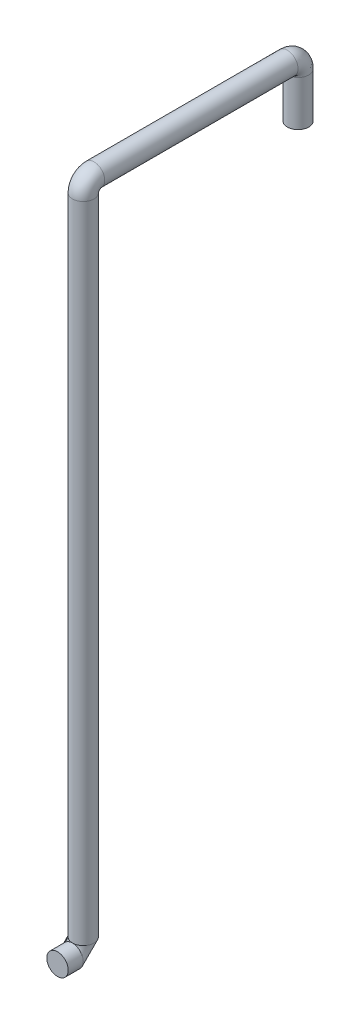
SolidWorks part; units mm, degrees
ref_plane "Alzado" through (0, 0, 0) normal (0, 0, 1) x (1, 0, 0)
ref_plane "Planta" through (0, 0, 0) normal (0, 1, 0) x (1, 0, 0)
ref_plane "Vista lateral" through (0, 0, 0) normal (1, 0, 0) x (0, 0, -1)
sketch "Croquis1" plane through (0, 0, 0) normal (0, 1, 0) x (1, 0, 0)
  circle A0 centre (0, 0) radius 50
  dimension "D1" = 100
extrude "Saliente-Extruir1" add sketch "Croquis1" along normal blind 10
sketch3d "Croquis3D1"
  line L0 (0, 10, 0) -> (0, 210, 0)
  line L1 (0, 10, 0) -> (0, 0, 0) construction
  line L2 (0, 260, 50) -> (0, 260, 950)
  line L3 (0, 210, 1000) -> (0, -2790, 1000)
  line L4 (0, -2840, 1050) -> (0, -2840, 1120)
  arc A0 (0, -2790, 1000) -> (0, -2840, 1050) centre (0, -2790, 1050) ccw
  arc A1 (0, 260, 950) -> (0, 210, 1000) centre (0, 210, 950) ccw
  arc A2 (0, 210, 0) -> (0, 260, 50) centre (0, 210, 50) ccw
  point P9 (0, -2840, 1000)
  point P10 (-50, -2790, 1050)
  point P13 (0, 260, 1000)
  point P14 (50, 210, 950)
  point P17 (0, 260, 0)
  point P18 (50, 210, 50)
  dimension "D5" = 50
  dimension "D1" = 250
  dimension "D2" = 1000
  dimension "D3" = 3100
  dimension "D4" = 120
sketch "Croquis2" plane through (0, 10, 0) normal (0, 1, 0) x (1, 0, 0)
  circle A0 centre (0, 0) radius 50
sweep "Barrer1" add profiles "Croquis2" path "Croquis3D1"
